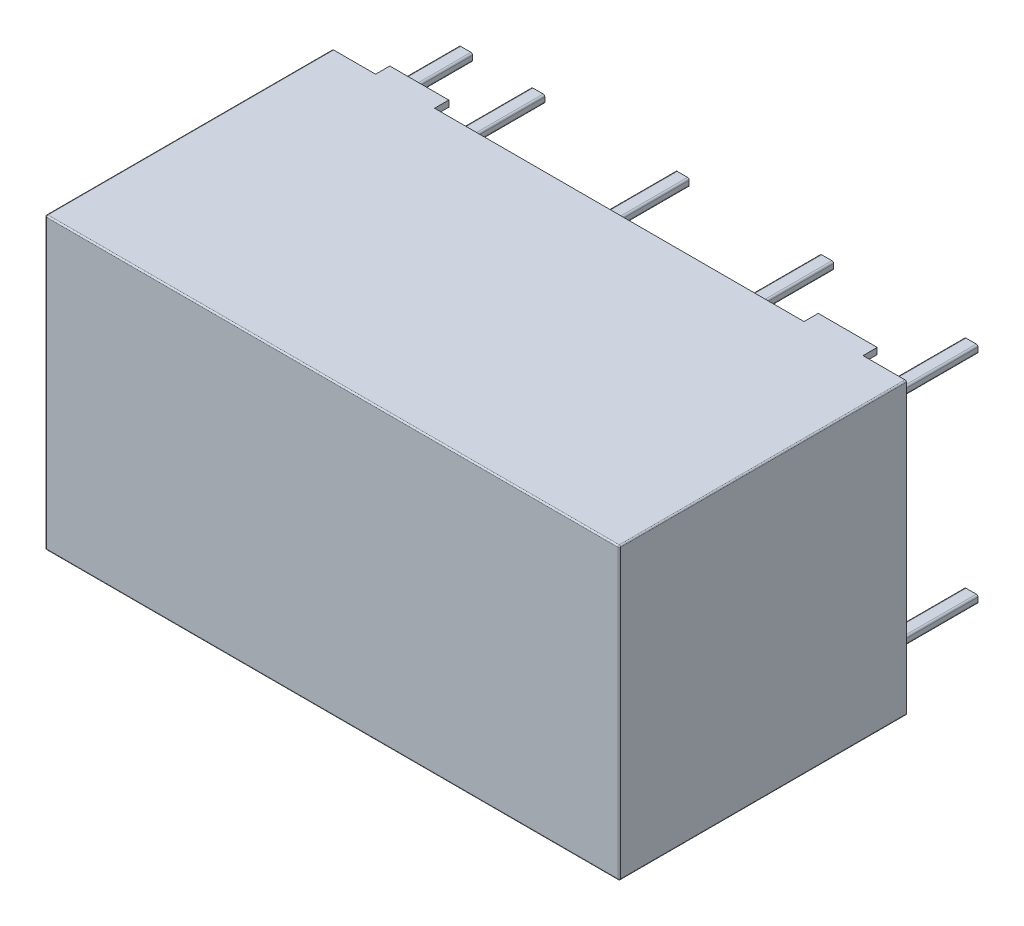
SolidWorks part; units mm, degrees
ref_plane "Front Plane" through (0, 0, 0) normal (0, 0, 1) x (1, 0, 0)
ref_plane "Top Plane" through (0, 0, 0) normal (0, 1, 0) x (1, 0, 0)
ref_plane "Right Plane" through (0, 0, 0) normal (1, 0, 0) x (0, 0, -1)
sketch "Sketch1" plane through (0, 0, 0) normal (0, 0, 1) x (1, 0, 0)
  line L1 (-10.1, 5.1) -> (10.1, 5.1)
  line L2 (-10.1, 5.1) -> (-10.1, -5.1)
  line L3 (-10.1, -5.1) -> (10.1, -5.1)
  line L4 (10.1, 5.1) -> (10.1, -5.1)
  line L5 (-10.1, 5.1) -> (10.1, -5.1) construction
  line L6 (-10.1, -5.1) -> (10.1, 5.1) construction
  point P0 (0, 0)
  dimension "D1" = 20.2
  dimension "D2" = 10.2
extrude "Boss-Extrude1" add sketch "Sketch1" along normal blind 10.6
sketch "Sketch2" plane through (0, 0, 0) normal (0, 0, -1) x (-1, 0, 0)
  line L0 (10.1, -5.1) -> (-10.1, -5.1) construction
  line L1 (6.5, -5.1) -> (-6.5, -5.1)
  line L2 (6.5, -5.1) -> (6.5, 5.1)
  line L3 (6.5, 5.1) -> (-6.5, 5.1)
  line L4 (-6.5, -5.1) -> (-6.5, 5.1)
  line L5 (6.5, -5.1) -> (-6.5, 5.1) construction
  line L6 (6.5, 5.1) -> (-6.5, -5.1) construction
  line L7 (-10.1, 5.1) -> (10.1, 5.1) construction
  line L9 (-10.1, -5.1) -> (-8.575, -5.1)
  line L10 (-10.1, -5.1) -> (-10.1, 5.1)
  line L11 (-10.1, 5.1) -> (-8.575, 5.1)
  line L12 (-8.575, -5.1) -> (-8.575, 5.1)
  line L13 (-10.1, -5.1) -> (-8.575, 5.1) construction
  line L14 (-10.1, 5.1) -> (-8.575, -5.1) construction
  line L15 (10.1, -5.1) -> (8.575, -5.1)
  line L16 (10.1, -5.1) -> (10.1, 5.1)
  line L17 (10.1, 5.1) -> (8.575, 5.1)
  line L18 (8.575, -5.1) -> (8.575, 5.1)
  line L19 (10.1, -5.1) -> (8.575, 5.1) construction
  line L20 (10.1, 5.1) -> (8.575, -5.1) construction
  point P4 (0, 0)
  point P13 (-9.3375, 0)
  point P19 (9.3375, 0)
  point P21 (0, 0)
  point P23 (4.0477, 5.1)
  point P24 (7.7014, 5.1)
  dimension "D1" = 17.15
  dimension "D2" = 13
extrude "Cut-Extrude1" cut sketch "Sketch2" against normal blind 0.5
sketch "Sketch3" plane through (0, 0, 0) normal (0, 0, -1) x (-1, 0, 0)
  line L0 (-8.575, -5.1) -> (-8.575, 5.1) construction
  line L1 (8.575, -4.88) -> (-8.575, -4.88)
  line L2 (8.575, -4.88) -> (8.575, 4.88)
  line L3 (8.575, 4.88) -> (-8.575, 4.88)
  line L4 (-8.575, -4.88) -> (-8.575, 4.88)
  line L5 (8.575, -4.88) -> (-8.575, 4.88) construction
  line L6 (8.575, 4.88) -> (-8.575, -4.88) construction
  line L7 (6.5, 5.1) -> (8.575, 5.1) construction
  point P0 (0, 0)
  dimension "D1" = 0.22
extrude "Cut-Extrude2" cut sketch "Sketch3" against normal up to surface (0.5 mm away) contours L2 L1 L4 L3 up to face at (0, 0, 0.5)
sketch "Sketch4" plane through (0, 0, 0.5) normal (0, 0, -1) x (-1, 0, 0)
  line L0 (10.1, -5.1) -> (10.1, 5.1) construction
  line L3 (9.14, -3.945) -> (8.66, -3.945)
  line L4 (9.14, -3.945) -> (9.14, -3.675)
  line L5 (9.14, -3.675) -> (8.66, -3.675)
  line L6 (8.66, -3.945) -> (8.66, -3.675)
  line L7 (9.14, -3.945) -> (8.66, -3.675) construction
  line L8 (9.14, -3.675) -> (8.66, -3.945) construction
  line L10 (6.6, -3.945) -> (6.12, -3.945)
  line L11 (6.6, -3.945) -> (6.6, -3.675)
  line L12 (6.6, -3.675) -> (6.12, -3.675)
  line L13 (6.12, -3.945) -> (6.12, -3.675)
  line L14 (6.6, -3.945) -> (6.12, -3.675) construction
  line L15 (6.6, -3.675) -> (6.12, -3.945) construction
  line L16 (1.52, -3.945) -> (1.04, -3.945)
  line L17 (1.52, -3.945) -> (1.52, -3.675)
  line L18 (1.52, -3.675) -> (1.04, -3.675)
  line L19 (1.04, -3.945) -> (1.04, -3.675)
  line L20 (1.52, -3.945) -> (1.04, -3.675) construction
  line L21 (1.52, -3.675) -> (1.04, -3.945) construction
  line L22 (-3.56, -3.945) -> (-4.04, -3.945)
  line L23 (-3.56, -3.945) -> (-3.56, -3.675)
  line L24 (-3.56, -3.675) -> (-4.04, -3.675)
  line L25 (-4.04, -3.945) -> (-4.04, -3.675)
  line L26 (-3.56, -3.945) -> (-4.04, -3.675) construction
  line L27 (-3.56, -3.675) -> (-4.04, -3.945) construction
  line L28 (-8.64, -3.945) -> (-9.12, -3.945)
  line L29 (-8.64, -3.945) -> (-8.64, -3.675)
  line L30 (-8.64, -3.675) -> (-9.12, -3.675)
  line L31 (-9.12, -3.945) -> (-9.12, -3.675)
  line L32 (-8.64, -3.945) -> (-9.12, -3.675) construction
  line L33 (-8.64, -3.675) -> (-9.12, -3.945) construction
  point P4 (8.9, -3.81)
  point P7 (6.36, -3.81)
  point P12 (1.28, -3.81)
  point P17 (-3.8, -3.81)
  point P22 (-8.88, -3.81)
  dimension "D7" = 5.08
  dimension "D1" = 0.48
  dimension "D2" = 0.27
  dimension "D3" = 3.81
  dimension "D4" = 1.2
  dimension "D5" = 2.54
  dimension "D6" = 5.08
  dimension "D8" = 5.08
extrude "Boss-Extrude2" add sketch "Sketch4" along normal offset from surface (3.5 mm away) 3 up to face at (-7.5375, -4.99, 0) offset beyond the face yes
fillet "Fillet1" radius 0.06 20 edges at (-8.66, -3.675, -1.25) (-9.14, -3.675, -1.25) (-8.66, -3.945, -1.25) (-9.14, -3.945, -1.25) (8.64, -3.945, -1.25) (4.04, -3.675, -1.25) (-1.04, -3.675, -1.25) (-6.12, -3.675, -1.25) (8.64, -3.675, -1.25) (9.12, -3.945, -1.25) (9.12, -3.675, -1.25) (4.04, -3.945, -1.25) (-1.04, -3.945, -1.25) (-6.12, -3.945, -1.25) (-6.6, -3.675, -1.25) (-1.52, -3.675, -1.25) (3.56, -3.675, -1.25) (3.56, -3.945, -1.25) (-1.52, -3.945, -1.25) (-6.6, -3.945, -1.25)
mirror "Mirror1" about plane through (0, 0, 0) normal (0, 1, 0) of "Fillet1", "Boss-Extrude2"
fillet "Fillet2" radius 0.05 8 edges at (10.1, 5.1, 5.55) (10.1, 0, 10.6) (0, 5.1, 10.6) (-10.1, 5.1, 5.55) (10.1, -5.1, 5.55) (-10.1, 0, 10.6) (0, -5.1, 10.6) (-10.1, -5.1, 5.55)
